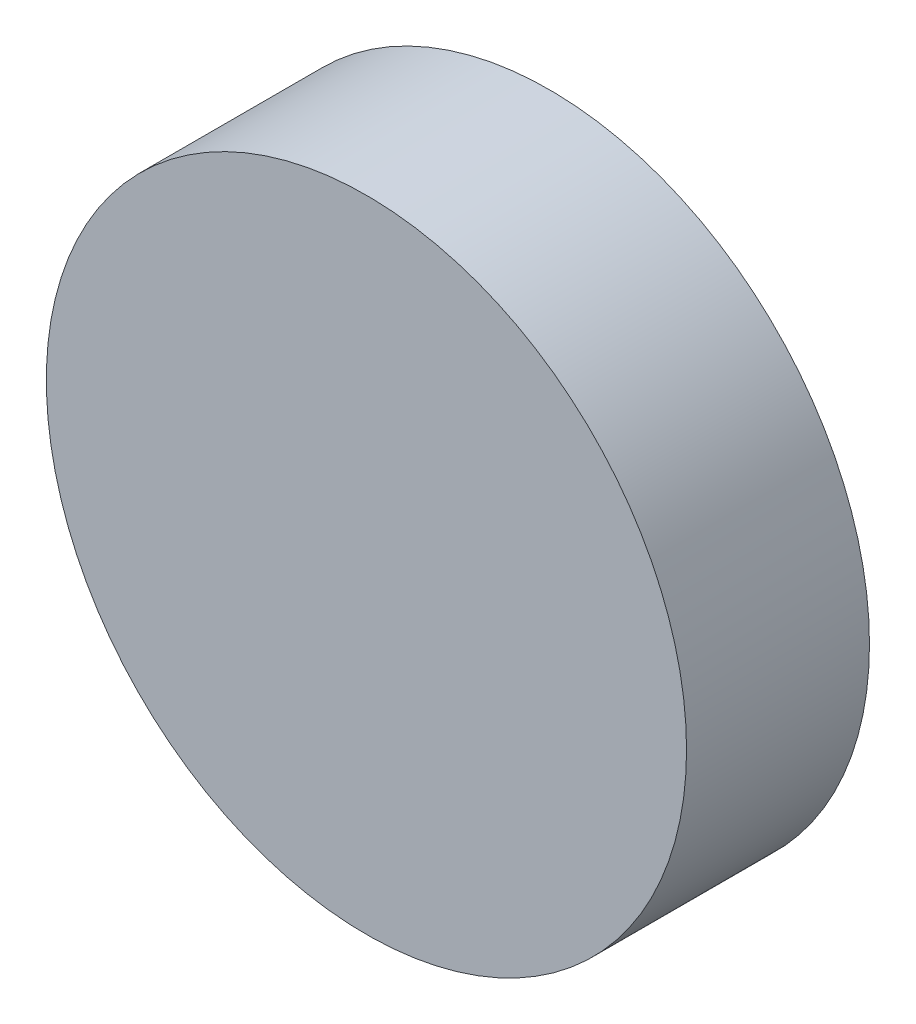
SolidWorks part; units mm, degrees
ref_plane "前视基准面" through (0, 0, 0) normal (0, 0, 1) x (1, 0, 0)
ref_plane "上视基准面" through (0, 0, 0) normal (0, 1, 0) x (1, 0, 0)
ref_plane "右视基准面" through (0, 0, 0) normal (1, 0, 0) x (0, 0, -1)
other "Configuration Table"
sketch "草图1" plane through (0, 0, 0) normal (0, 0, 1) x (1, 0, 0)
  circle A0 centre (0, 0) radius 70
  dimension "D1" = 140
extrude "凸台-拉伸1" add sketch "草图1" along normal blind 40
